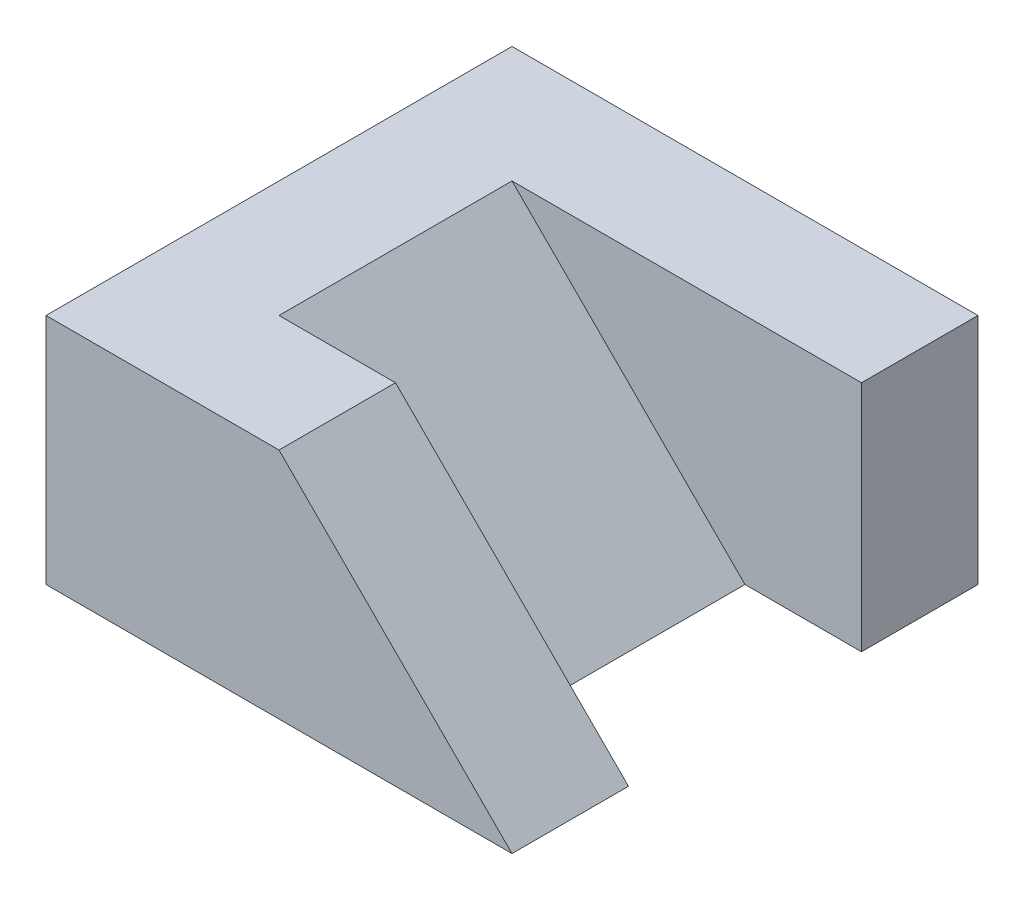
SolidWorks part; units mm, degrees
ref_plane "前基準面" through (0, 0, 0) normal (0, 0, 1) x (1, 0, 0)
ref_plane "上基準面" through (0, 0, 0) normal (0, 1, 0) x (1, 0, 0)
ref_plane "右基準面" through (0, 0, 0) normal (1, 0, 0) x (0, 0, -1)
sketch "草圖1" plane through (0, 0, 0) normal (0, 1, 0) x (1, 0, 0)
  line L0 (0, 0) -> (40, 0)
  line L1 (40, 0) -> (40, -10)
  line L2 (40, -10) -> (10, -10)
  line L3 (10, -10) -> (10, -30)
  line L4 (10, -30) -> (40, -30)
  line L5 (40, -30) -> (40, -40)
  line L6 (40, -40) -> (0, -40)
  line L7 (0, -40) -> (0, 0)
  dimension "D1" = 10
  dimension "D2" = 10
  dimension "D3" = 20
  dimension "D4" = 30
  dimension "D5" = 30
  dimension "D6" = 10
extrude "填料-伸長1" add sketch "草圖1" along normal blind 20
sketch "草圖2" plane through (0, 0, 10) normal (0, 0, 1) x (1, 0, 0)
  line L0 (10, 20) -> (30, 0)
  line L1 (0, 0) -> (40, 0) construction
  line L2 (10, 20) -> (10, 0)
  line L3 (10, 0) -> (30, 0)
  line L4 (40, 20) -> (40, 0) construction
  dimension "D1" = 10
extrude "填料-伸長2" add sketch "草圖2" along normal blind 20
sketch "草圖3" plane through (0, 0, 40) normal (0, 0, 1) x (1, 0, 0)
  line L0 (20, 20) -> (40, 0)
  line L1 (0, 20) -> (40, 20) construction
  line L2 (40, 0) -> (40, 20)
  line L3 (40, 20) -> (20, 20)
  dimension "D1" = 20
extrude "除料-伸長1" cut sketch "草圖3" against normal blind 20
